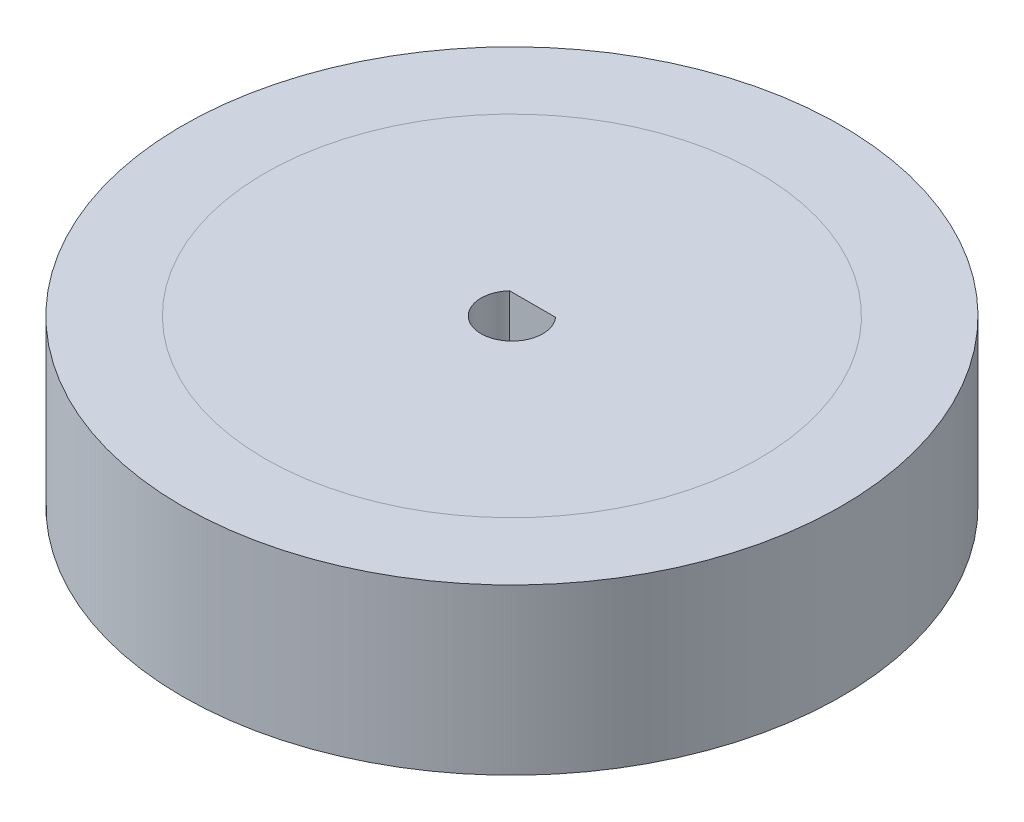
SolidWorks part; units mm, degrees
ref_plane "前视基准面" through (0, 0, 0) normal (0, 0, 1) x (1, 0, 0)
ref_plane "上视基准面" through (0, 0, 0) normal (0, 1, 0) x (1, 0, 0)
ref_plane "右视基准面" through (0, 0, 0) normal (1, 0, 0) x (0, 0, -1)
other "Configuration Table"
sketch "草图1" plane through (0, 0, 0) normal (0, 1, 0) x (1, 0, 0)
  line L0 (-1.118, 1) -> (1.118, 1)
  arc A0 (-1.118, 1) -> (1.118, 1) centre (0, 0) ccw
  circle A1 centre (0, 0) radius 12
  dimension "D1" = 3
  dimension "D3" = 24
  dimension "D2" = 1
extrude "凸台-拉伸1" add sketch "草图1" along normal blind 8
sketch "草图2" plane through (0, 8, 0) normal (0, 1, 0) x (1, 0, 0)
  circle A0 centre (0, 0) radius 16
  circle A1 centre (0, 0) radius 12
  circle A2 centre (0, 0) radius 12
  dimension "D1" = 0
  dimension "D2" = 4
extrude "凸台-拉伸2" add sketch "草图2" against normal up to surface (8 mm away) separate body up to face at (0, 0, 12)
